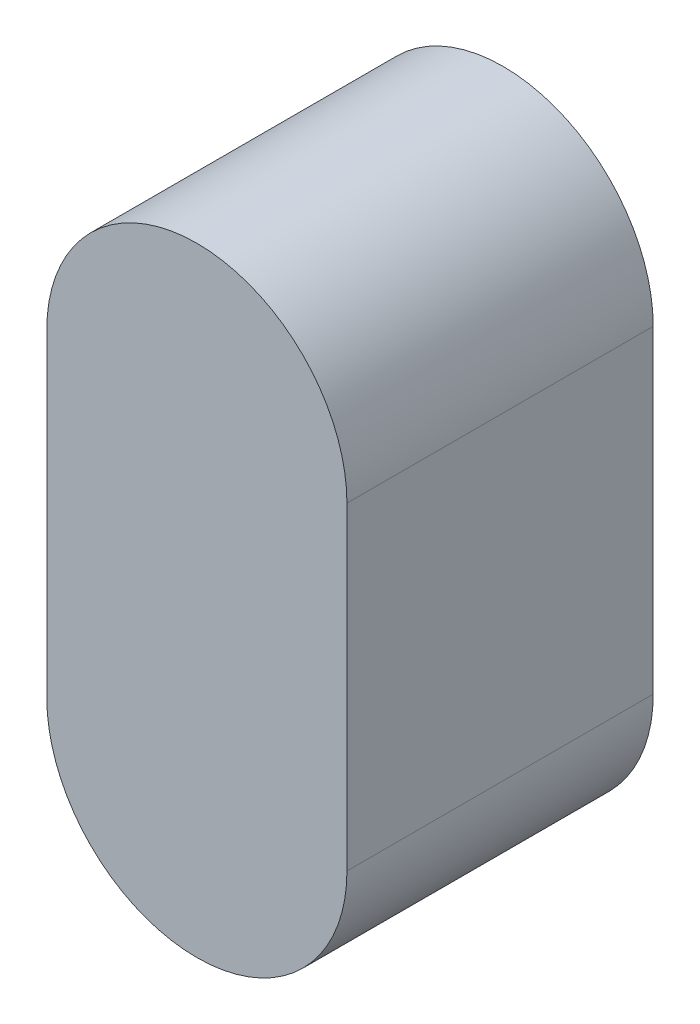
SolidWorks part; units mm, degrees
ref_plane "Front Plane" through (0, 0, 0) normal (0, 0, 1) x (1, 0, 0)
ref_plane "Top Plane" through (0, 0, 0) normal (0, 1, 0) x (1, 0, 0)
ref_plane "Right Plane" through (0, 0, 0) normal (1, 0, 0) x (0, 0, -1)
sketch "Sketch1" plane through (0, 0, 0) normal (0, 0, 1) x (1, 0, 0)
  line L4 (0, 20.2) -> (0, 0) construction
  line L6 (0, 4.9) -> (0, 15.3) construction
  line L7 (-4.9, 4.9) -> (-4.9, 15.3)
  line L8 (4.9, 4.9) -> (4.9, 15.3)
  arc A0 (-4.9, 4.9) -> (4.9, 4.9) centre (0, 4.9) ccw
  arc A1 (4.9, 15.3) -> (-4.9, 15.3) centre (0, 15.3) ccw
  point P14 (0, 10.1)
  point P19 (0, 0)
  dimension "D1" = 10.4
  dimension "D2" = 9.8
extrude "Boss-Extrude1" add sketch "Sketch1" along normal blind 10
